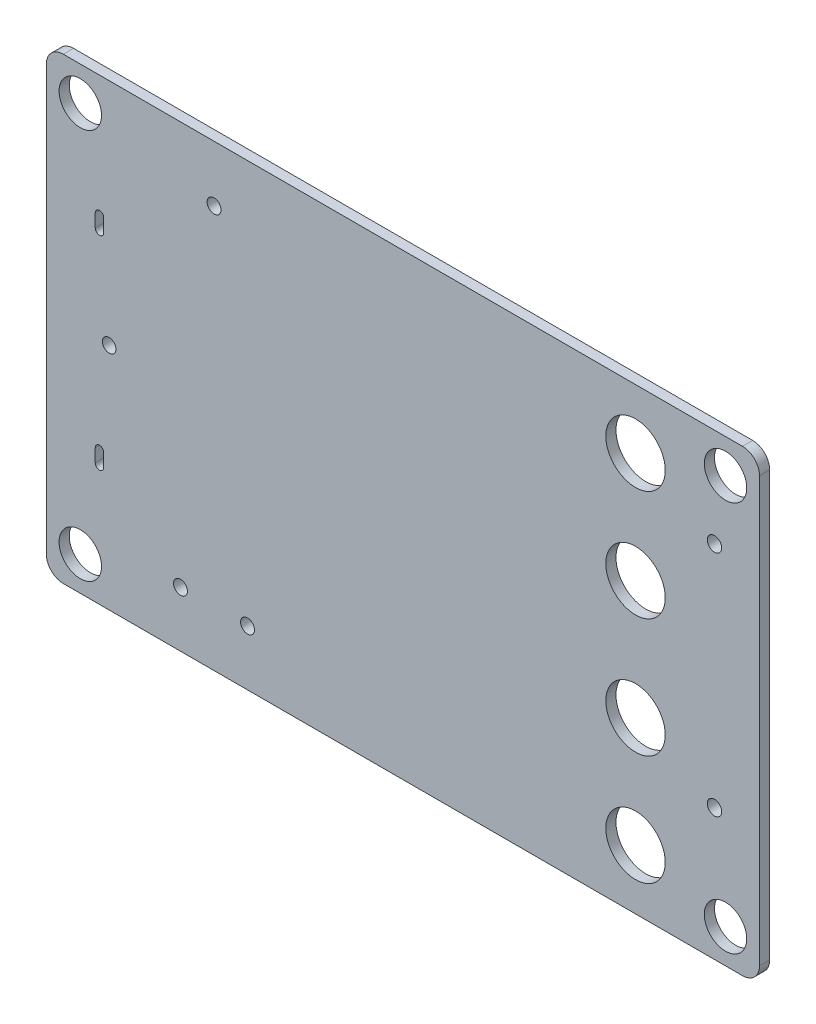
SolidWorks part; units mm, degrees
ref_plane "Front Plane" through (0, 0, 0) normal (0, 0, 1) x (1, 0, 0)
ref_plane "Top Plane" through (0, 0, 0) normal (0, 1, 0) x (1, 0, 0)
ref_plane "Right Plane" through (0, 0, 0) normal (1, 0, 0) x (0, 0, -1)
sketch "Sketch1" plane through (0, 0, 0) normal (0, 0, 1) x (1, 0, 0)
  line L1 (-53.34, -34.29) -> (53.34, -34.29)
  line L2 (-53.34, -34.29) -> (-53.34, 34.29)
  line L3 (-53.34, 34.29) -> (53.34, 34.29)
  line L4 (53.34, -34.29) -> (53.34, 34.29)
  line L5 (-53.34, -34.29) -> (53.34, 34.29) construction
  line L6 (-53.34, 34.29) -> (53.34, -34.29) construction
  point P0 (0, 0)
  dimension "D1" = 68.58
  dimension "D2" = 106.68
extrude "Boss-Extrude1" add sketch "Sketch1" along normal blind 1.524
sketch "Sketch2" plane through (0, 0, 1.524) normal (0, 0, 1) x (1, 0, 0)
  line L0 (0, 0) -> (71.1757, 0) construction
  line L1 (0.8382, 0) -> (-0.8382, 0) construction
  line L2 (0, 0) -> (0, -48.0326) construction
  circle A0 centre (-48.26, 29.21) radius 3.175
  circle A1 centre (-48.26, -29.21) radius 3.175
  circle A2 centre (48.26, -29.21) radius 3.175
  circle A3 centre (48.26, 29.21) radius 3.175
  dimension "D2" = 58.42
  dimension "D3" = 6.35
  dimension "D1" = 96.52
extrude "Cut-Extrude1" cut sketch "Sketch2" against normal up to next
sketch "Sketch3" plane through (0, 0, 1.524) normal (0, 0, 1) x (1, 0, 0)
  line L0 (-53.34, -34.29) -> (53.34, -34.29) construction
  line L1 (53.34, -34.29) -> (53.34, 34.29) construction
  circle A0 centre (34.798, -25.4) radius 4.445
  circle A1 centre (34.798, -8.89) radius 4.445
  circle A2 centre (34.798, 8.89) radius 4.445
  circle A3 centre (34.798, 25.4) radius 4.445
  dimension "D2" = 16.51
  dimension "D3" = 17.78
  dimension "D4" = 16.51
  dimension "D6" = 8.89
  dimension "D1" = 8.89
  dimension "D5" = 18.542
extrude "Cut-Extrude2" cut sketch "Sketch3" against normal up to next
fillet "Fillet1" radius 2.54 4 edges at (53.34, 34.29, 0.762) (53.34, -34.29, 0.762) (-53.34, -34.29, 0.762) (-53.34, 34.29, 0.762)
sketch "Sketch4" plane through (0, 0, 1.524) normal (0, 0, 1) x (1, 0, 0)
  line L0 (53.34, -31.75) -> (53.34, 31.75) construction
  line L1 (-50.8, -34.29) -> (50.8, -34.29) construction
  line L2 (50.8, 34.29) -> (-50.8, 34.29) construction
  line L3 (-53.34, 31.75) -> (-53.34, -31.75) construction
  circle A0 centre (-23.241, -26.0096) radius 1.0414
  circle A1 centre (-33.274, -26.0096) radius 1.0414
  circle A2 centre (-28.2448, 25.908) radius 1.0414
  circle A3 centre (46.609, 19.558) radius 1.0795
  circle A4 centre (46.609, -14.605) radius 1.0795
  dimension "D3" = 2.159
  dimension "D5" = 34.163
  dimension "D6" = 8.2804
  dimension "D7" = 20.066
  dimension "D8" = 2.0828
  dimension "D9" = 10.033
  dimension "D11" = 25.0952
  dimension "D1" = 6.731
  dimension "D2" = 19.685
  dimension "D4" = 14.732
  dimension "D10" = 8.382
extrude "Cut-Extrude3" cut sketch "Sketch4" against normal up to next
sketch "Sketch5" plane through (0, 0, 1.524) normal (0, 0, 1) x (1, 0, 0)
  line L0 (0.8382, 0) -> (-0.8382, 0) construction
  line L1 (-53.34, 31.75) -> (-53.34, -31.75) construction
  circle A0 centre (-43.942, 0) radius 1.016
  dimension "D1" = 2.032
  dimension "D2" = 9.398
extrude "Cut-Extrude4" cut sketch "Sketch5" against normal up to next
sketch "Sketch6" plane through (0, 0, 1.524) normal (0, 0, 1) x (1, 0, 0)
  line L0 (-45.3898, 16.129) -> (-45.3898, 14.1732) construction
  line L1 (-44.7548, 16.129) -> (-44.7548, 14.1732)
  line L2 (-46.0248, 16.129) -> (-46.0248, 14.1732)
  line L3 (-53.34, 31.75) -> (-53.34, -31.75) construction
  line L4 (50.8, 34.29) -> (-50.8, 34.29) construction
  line L5 (-45.3898, -14.3002) -> (-45.3898, -16.256) construction
  line L6 (-44.7548, -14.3002) -> (-44.7548, -16.256)
  line L7 (-46.0248, -14.3002) -> (-46.0248, -16.256)
  line L8 (-50.8, -34.29) -> (50.8, -34.29) construction
  arc A0 (-44.7548, 16.129) -> (-46.0248, 16.129) centre (-45.3898, 16.129) ccw
  arc A1 (-46.0248, 14.1732) -> (-44.7548, 14.1732) centre (-45.3898, 14.1732) ccw
  arc A2 (-44.7548, -14.3002) -> (-46.0248, -14.3002) centre (-45.3898, -14.3002) ccw
  arc A3 (-46.0248, -16.256) -> (-44.7548, -16.256) centre (-45.3898, -16.256) ccw
  point P2 (-45.3898, 15.1511)
  point P13 (-45.3898, -15.2781)
  dimension "D1" = 1.27
  dimension "D2" = 1.9558
  dimension "D3" = 7.9502
  dimension "D4" = 18.161
  dimension "D5" = 18.034
extrude "Cut-Extrude5" cut sketch "Sketch6" against normal up to next
